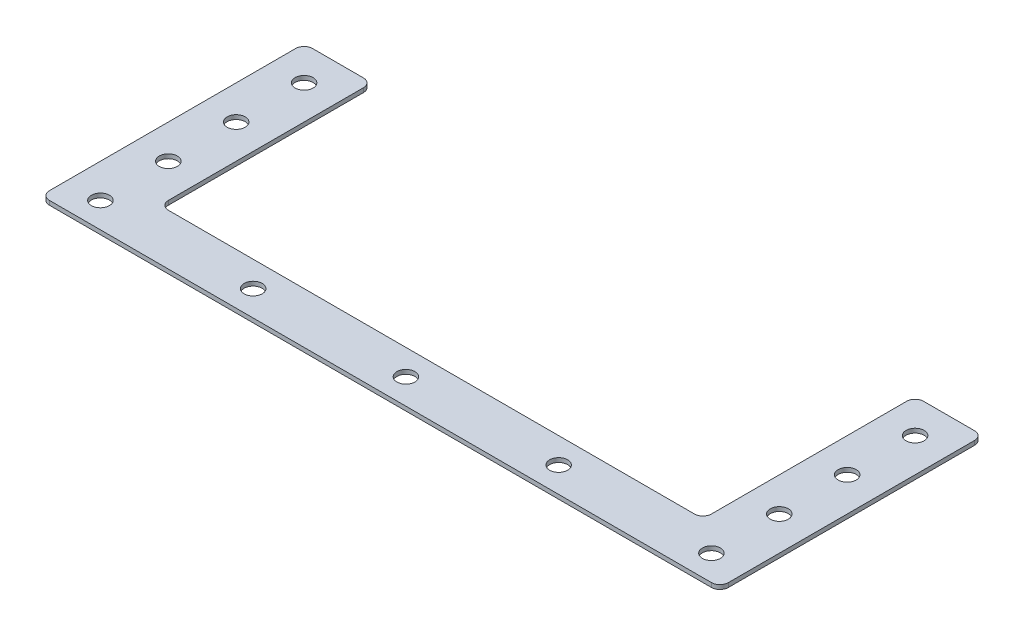
SolidWorks part; units mm, degrees
ref_plane "Front Plane" through (0, 0, 0) normal (0, 0, 1) x (1, 0, 0)
ref_plane "Top Plane" through (0, 0, 0) normal (0, 1, 0) x (1, 0, 0)
ref_plane "Right Plane" through (0, 0, 0) normal (1, 0, 0) x (0, 0, -1)
sketch "Sketch1" plane through (0, 0, 0) normal (0, 1, 0) x (1, 0, 0)
  line L1 (-127, 49.2125) -> (-101.6, 49.2125)
  line L2 (-127, 49.2125) -> (-127, -49.2125)
  line L3 (-127, -49.2125) -> (-101.6, -49.2125)
  line L4 (-101.6, 49.2125) -> (-101.6, -49.2125)
  line L5 (-101.6, -49.2125) -> (101.6, -49.2125)
  line L6 (-101.6, -49.2125) -> (-101.6, -30.1625)
  line L7 (-101.6, -30.1625) -> (101.6, -30.1625)
  line L8 (101.6, -49.2125) -> (101.6, -30.1625)
  line L9 (101.6, -49.2125) -> (127, -49.2125)
  line L10 (101.6, -49.2125) -> (101.6, 49.2125)
  line L11 (101.6, 49.2125) -> (127, 49.2125)
  line L12 (127, -49.2125) -> (127, 49.2125)
  point P10 (0, -30.1625)
  point P12 (101.6, 0)
  dimension "D1" = 25.4
  dimension "D2" = 19.05
  dimension "D3" = 98.425
  dimension "D4" = 254
extrude "Boss-Extrude1" add sketch "Sketch1" along normal blind 1.5875 contours L4 L1 L2 L3 | L5 L8 L7 L4 | L9 L12 L11 L10 L8
fillet "Fillet2" radius 3.175 8 edges at (-127, 0.7937, 49.2125) (-127, 0.7937, -49.2125) (101.6, 0.7937, 30.1625) (127, 0.7937, 49.2125) (101.6, 0.7937, -49.2125) (127, 0.7937, -49.2125) (-101.6, 0.7937, 30.1625) (-101.6, 0.7937, -49.2125)
sketch "Sketch2" plane through (0, 1.5875, 0) normal (0, 1, 0) x (1, 0, 0)
  line L8 (-127, 46.0375) -> (-127, -46.0375)
  line L9 (-123.825, -49.2125) -> (123.825, -49.2125)
  line L10 (127, -46.0375) -> (127, 46.0375)
  line L11 (123.825, 49.2125) -> (104.775, 49.2125)
  line L12 (101.6, 46.0375) -> (101.6, -26.9875)
  line L13 (98.425, -30.1625) -> (-98.425, -30.1625)
  line L14 (-101.6, -26.9875) -> (-101.6, 46.0375)
  line L15 (-104.775, 49.2125) -> (-123.825, 49.2125)
  line L16 (-127, 46.0375) -> (-127, -46.0375)
  line L17 (-123.825, -49.2125) -> (123.825, -49.2125)
  line L18 (127, -46.0375) -> (127, 46.0375)
  line L19 (123.825, 49.2125) -> (104.775, 49.2125)
  line L20 (101.6, 46.0375) -> (101.6, -26.9875)
  line L21 (98.425, -30.1625) -> (-98.425, -30.1625)
  line L22 (-101.6, -26.9875) -> (-101.6, 46.0375)
  line L23 (-104.775, 49.2125) -> (-123.825, 49.2125)
  circle A0 centre (-114.3, 36.5125) radius 6.35 construction
  circle A1 centre (-114.3, 11.1125) radius 6.35 construction
  circle A2 centre (-114.3, -14.2875) radius 6.35 construction
  circle A3 centre (-57.15, -39.6875) radius 6.35 construction
  circle A4 centre (0, -39.6875) radius 6.35 construction
  circle A5 centre (57.15, -39.6875) radius 6.35 construction
  circle A6 centre (114.3, -14.2875) radius 6.35 construction
  circle A7 centre (114.3, 11.1125) radius 6.35 construction
  arc A8 (-127, -46.0375) -> (-123.825, -49.2125) centre (-123.825, -46.0375) ccw
  arc A9 (123.825, -49.2125) -> (127, -46.0375) centre (123.825, -46.0375) ccw
  arc A10 (127, 46.0375) -> (123.825, 49.2125) centre (123.825, 46.0375) ccw
  arc A11 (104.775, 49.2125) -> (101.6, 46.0375) centre (104.775, 46.0375) ccw
  arc A12 (98.425, -30.1625) -> (101.6, -26.9875) centre (98.425, -26.9875) ccw
  arc A13 (-101.6, -26.9875) -> (-98.425, -30.1625) centre (-98.425, -26.9875) ccw
  arc A14 (-101.6, 46.0375) -> (-104.775, 49.2125) centre (-104.775, 46.0375) ccw
  arc A15 (-123.825, 49.2125) -> (-127, 46.0375) centre (-123.825, 46.0375) ccw
  arc A16 (-127, -46.0375) -> (-123.825, -49.2125) centre (-123.825, -46.0375) ccw
  arc A17 (123.825, -49.2125) -> (127, -46.0375) centre (123.825, -46.0375) ccw
  arc A18 (127, 46.0375) -> (123.825, 49.2125) centre (123.825, 46.0375) ccw
  arc A19 (104.775, 49.2125) -> (101.6, 46.0375) centre (104.775, 46.0375) ccw
  arc A20 (98.425, -30.1625) -> (101.6, -26.9875) centre (98.425, -26.9875) ccw
  arc A21 (-101.6, -26.9875) -> (-98.425, -30.1625) centre (-98.425, -26.9875) ccw
  arc A22 (-101.6, 46.0375) -> (-104.775, 49.2125) centre (-104.775, 46.0375) ccw
  arc A23 (-123.825, 49.2125) -> (-127, 46.0375) centre (-123.825, 46.0375) ccw
  circle A24 centre (114.3, 36.5125) radius 6.35 construction
  circle A25 centre (-114.3, 11.1125) radius 6.35 construction
  circle A26 centre (114.3, -39.6875) radius 6.35 construction
  circle A27 centre (-114.3, -39.6875) radius 6.35 construction
  point P57 (101.6, -39.6875)
  dimension "D1" = 0
hole_wizard "Tap Drill for 1/4 Helicoil0" positions "Sketch3" profile "Sketch4" hole size "1/4-20" standard "ANSI Inch" end condition through all
sketch "Sketch3" plane through (0, 1.5875, 0) normal (0, 1, 0) x (1, 0, 0)
  point P0 (-114.3, 36.5125)
  point P3 (-114.3, 11.1125)
  point P6 (-114.3, -14.2875)
  point P9 (-57.15, -39.6875)
  point P12 (0, -39.6875)
  point P15 (57.15, -39.6875)
  point P18 (114.3, -14.2875)
  point P21 (114.3, 11.1125)
  point P24 (114.3, 36.5125)
  point P27 (-114.3, -39.6875)
  point P30 (114.3, -39.6875)
sketch "Sketch4" plane through (-114.3, 1.5875, -36.5125) normal (1, 0, 0) x (0, 0, 1)
  line L0 (0, 0) -> (0, 1.5875)
  line L1 (0, 1.5875) -> (3.3782, 1.5875)
  line L2 (3.3782, 1.5875) -> (3.3782, 0)
  line L5 (3.3782, 0) -> (0, 0)
  line L11 (0, -6.35) -> (0, 107.95) construction
  dimension "Thru Hole Dia." = 6.7564
  dimension "Thru Hole Depth" = 1.5875
